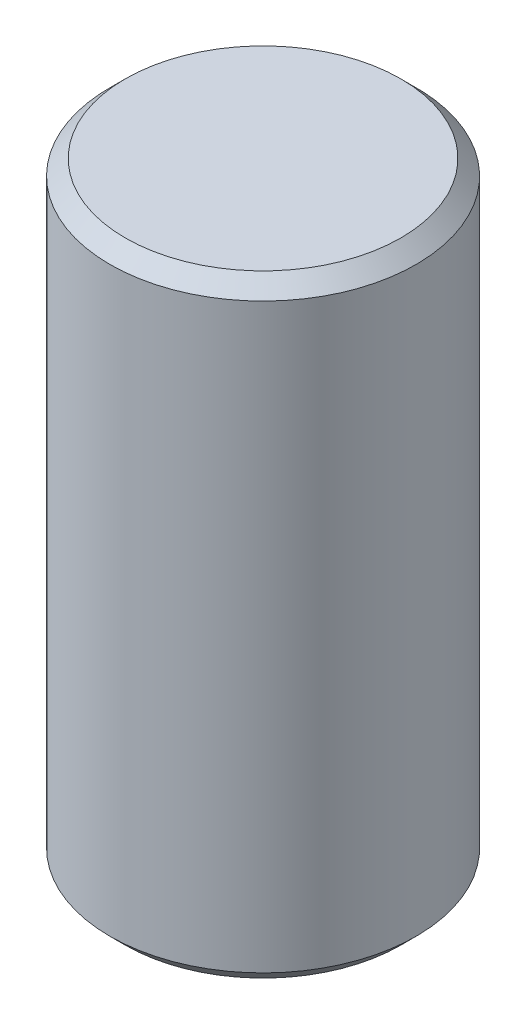
SolidWorks part; units mm, degrees
material "1.4401 (X5CrNiMo17-12-2)"
ref_plane "Front Plane" through (0, 0, 0) normal (0, 0, 1) x (1, 0, 0)
ref_plane "Top Plane" through (0, 0, 0) normal (0, 1, 0) x (1, 0, 0)
ref_plane "Right Plane" through (0, 0, 0) normal (1, 0, 0) x (0, 0, -1)
sketch "Sketch1" plane through (0, 0, 0) normal (0, 1, 0) x (1, 0, 0)
  circle A0 centre (0, 0) radius 2.5
  dimension "D1" = 5
extrude "Boss-Extrude1" add sketch "Sketch1" along normal blind 10
chamfer "Chamfer1" distance 0.25 angle 45 2 edges at (0, 0, 2.5) (0, 10, 2.5)
